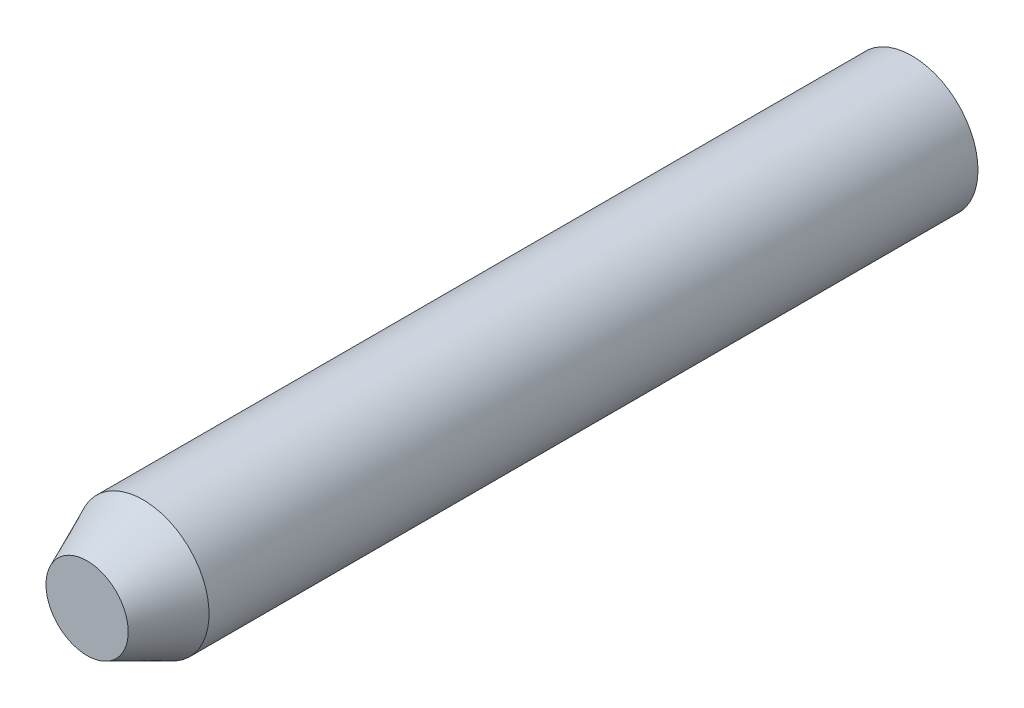
SolidWorks part; units mm, degrees
ref_plane "Front Plane" through (0, 0, 0) normal (0, 0, 1) x (1, 0, 0)
ref_plane "Top Plane" through (0, 0, 0) normal (0, 1, 0) x (1, 0, 0)
ref_plane "Right Plane" through (0, 0, 0) normal (1, 0, 0) x (0, 0, -1)
sketch "Sketch1" plane through (0, 0, 0) normal (0, 0, 1) x (1, 0, 0)
  circle A0 centre (0, 0) radius 8
extrude "Boss-Extrude1" add sketch "Sketch1" along normal blind 100
sketch "Sketch2" plane through (0, 0, 0) normal (1, 0, 0) x (0, 0, -1)
  line L0 (-100, 0) -> (-105.844, 0) construction
  line L1 (-100, 8) -> (-100, -8) construction
  line L2 (-100, 4.9831) -> (-100, 8)
  line L3 (-100, 8) -> (-93.2144, 8)
  line L4 (0, 8) -> (-100, 8) construction
  line L5 (-100, 4.9831) -> (-93.2144, 8)
revolve "Cut-Revolve2" cut sketch "Sketch2" angle 360 about L0
